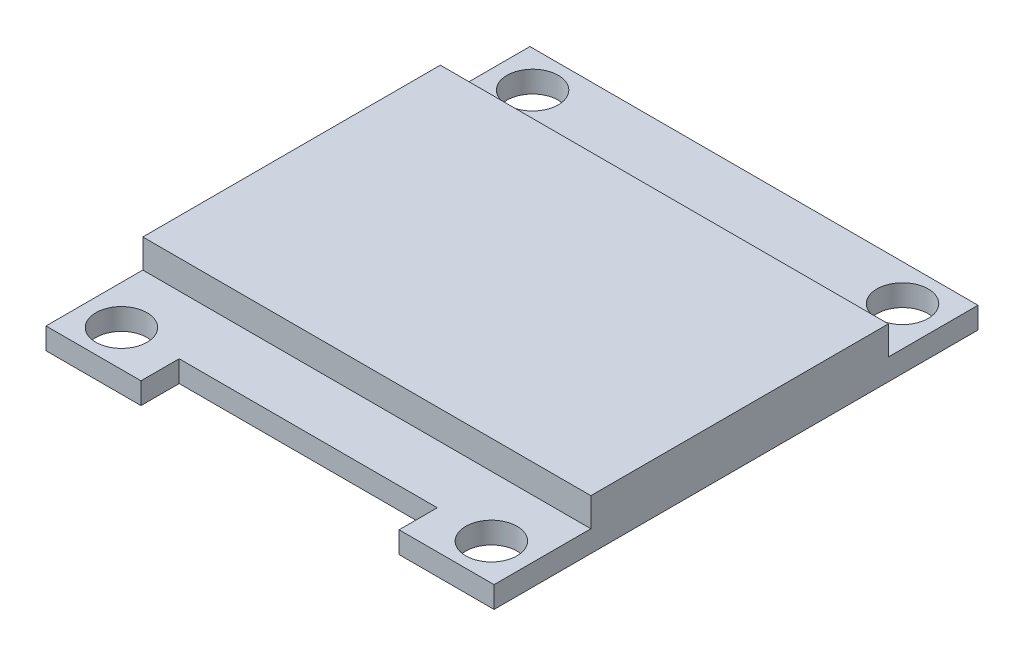
SolidWorks part; units mm, degrees
ref_plane "Front Plane" through (0, 0, 0) normal (0, 0, 1) x (1, 0, 0)
ref_plane "Top Plane" through (0, 0, 0) normal (0, 1, 0) x (1, 0, 0)
ref_plane "Right Plane" through (0, 0, 0) normal (1, 0, 0) x (0, 0, -1)
sketch "Sketch1" plane through (0, 0, 0) normal (0, 1, 0) x (1, 0, 0)
  line L1 (-12.5, -13.5) -> (12.5, -13.5)
  line L2 (-12.5, -13.5) -> (-12.5, 13.5)
  line L3 (-12.5, 13.5) -> (12.5, 13.5)
  line L4 (12.5, -13.5) -> (12.5, 13.5)
  line L5 (-12.5, -13.5) -> (12.5, 13.5) construction
  line L6 (-12.5, 13.5) -> (12.5, -13.5) construction
  point P0 (0, 0)
  dimension "D1" = 25
  dimension "D2" = 27
extrude "Boss-Extrude1" add sketch "Sketch1" along normal blind 1.2
sketch "Sketch2" plane through (0, 1.2, 0) normal (0, 1, 0) x (1, 0, 0)
  line L0 (12.5, -13.5) -> (12.5, 13.5) construction
  line L1 (12.5, 8.5) -> (-12.5, 8.5)
  line L2 (12.5, 8.5) -> (12.5, -8.1)
  line L3 (12.5, -8.1) -> (-12.5, -8.1)
  line L4 (-12.5, 8.5) -> (-12.5, -8.1)
  line L5 (-12.5, 13.5) -> (-12.5, -13.5) construction
  line L6 (12.5, 13.5) -> (-12.5, 13.5) construction
  dimension "D1" = 16.6
  dimension "D2" = 5
extrude "Boss-Extrude2" add sketch "Sketch2" along normal blind 1.6
sketch "Sketch3" plane through (0, 1.2, 0) normal (0, 1, 0) x (1, 0, 0)
  line L0 (-12.5, 13.5) -> (-12.5, 8.5) construction
  line L1 (11.75, 9.1655) -> (11.75, 12.2077) construction
  line L2 (12.5, 8.5) -> (12.5, 13.5) construction
  line L3 (8.8663, 12.9) -> (11.6199, 12.9) construction
  line L4 (12.5, 13.5) -> (-12.5, 13.5) construction
  line L5 (-12.5, -13.5) -> (12.5, -13.5) construction
  line L6 (12.5, -13.5) -> (12.5, -8.1) construction
  line L7 (-12.5, -8.1) -> (-12.5, -13.5) construction
  line L9 (-7.2, -13.5) -> (7.2, -13.5)
  line L10 (-7.2, -13.5) -> (-7.2, -11.37)
  line L11 (-7.2, -11.37) -> (7.2, -11.37)
  line L12 (7.2, -13.5) -> (7.2, -11.37)
  circle A0 centre (10.32, 11.47) radius 1.43
  circle A1 centre (-10.32, 11.47) radius 1.43
  circle A2 centre (-10.32, -11.47) radius 1.43
  circle A3 centre (10.32, -11.47) radius 1.43
  point P28 (0, -13.5)
  point P29 (0, -13.5)
  dimension "D1" = 2.86
  dimension "D2" = 0.75
  dimension "D3" = 0.6
  dimension "D4" = 2.18
  dimension "D5" = 2.03
  dimension "D6" = 2.03
  dimension "D7" = 2.18
  dimension "D8" = 2.03
  dimension "D9" = 2.18
  dimension "D10" = 14.4
  dimension "D11" = 2.13
extrude "Cut-Extrude1" cut sketch "Sketch3" against normal up to surface (1.2 mm away) up to face at (0, 0, 0)
